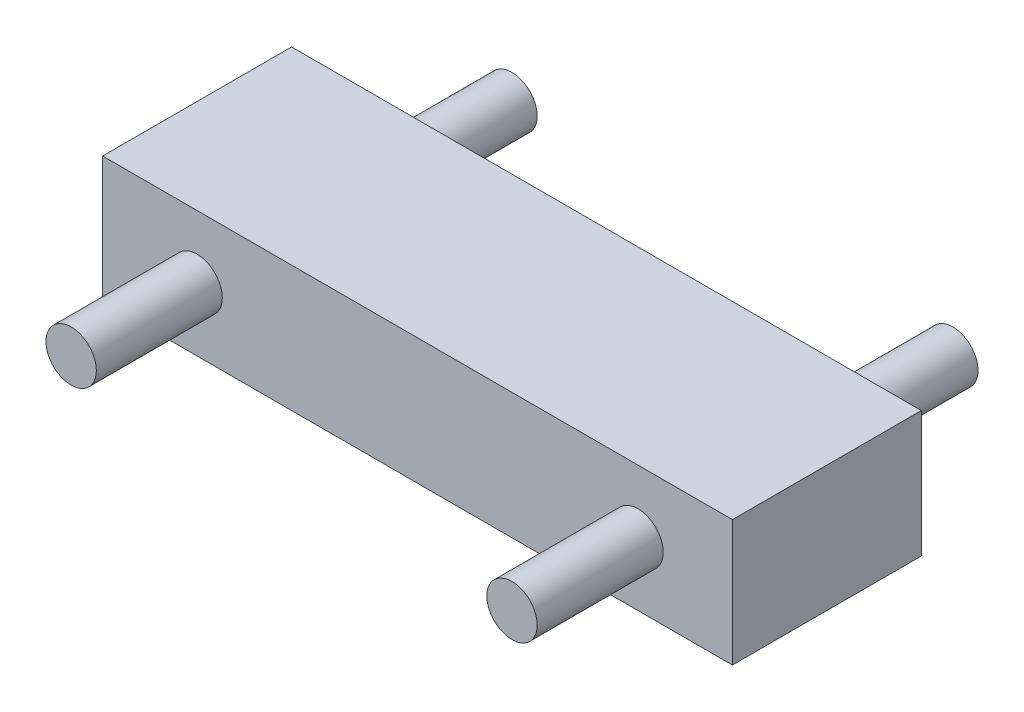
SolidWorks part; units mm, degrees
ref_plane "Front Plane" through (0, 0, 0) normal (0, 0, 1) x (1, 0, 0)
ref_plane "Top Plane" through (0, 0, 0) normal (0, 1, 0) x (1, 0, 0)
ref_plane "Right Plane" through (0, 0, 0) normal (1, 0, 0) x (0, 0, -1)
sketch "Sketch2" plane through (0, 0, 0) normal (0, 1, 0) x (1, 0, 0)
  line L1 (-500, -150) -> (500, -150)
  line L2 (-500, -150) -> (-500, 150)
  line L3 (-500, 150) -> (500, 150)
  line L4 (500, -150) -> (500, 150)
  line L5 (-500, -150) -> (500, 150) construction
  line L6 (-500, 150) -> (500, -150) construction
  point P0 (0, 0)
  dimension "D1" = 1000
  dimension "D2" = 300
extrude "Boss-Extrude1" add sketch "Sketch2" against normal blind 200
sketch "Sketch3" plane through (0, 0, 150) normal (0, 0, 1) x (1, 0, 0)
  line L0 (-500, 0) -> (500, 0) construction
  circle A0 centre (-350, -100) radius 40
  circle A1 centre (350, -100) radius 40
  point P4 (0, 0)
  dimension "D3" = 80
  dimension "D4" = 80
  dimension "D5" = 100
  dimension "D1" = 350
  dimension "D2" = 350
extrude "Boss-Extrude2" add sketch "Sketch3" along normal blind 200
sketch "Sketch5" plane through (0, 0, -150) normal (0, 0, -1) x (-1, 0, 0)
  circle A0 centre (-350, -100) radius 40
  circle A1 centre (350, -100) radius 40
  point P4 (0, 0)
  dimension "D1" = 80
  dimension "D2" = 80
  dimension "D3" = 100
  dimension "D4" = 350
  dimension "D5" = 350
extrude "Boss-Extrude3" add sketch "Sketch5" along normal blind 200
